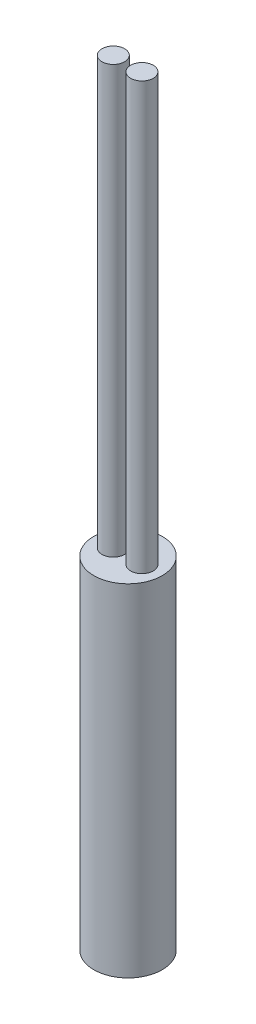
SolidWorks part; units mm, degrees
ref_plane "前视基准面" through (0, 0, 0) normal (0, 0, 1) x (1, 0, 0)
ref_plane "上视基准面" through (0, 0, 0) normal (0, 1, 0) x (1, 0, 0)
ref_plane "右视基准面" through (0, 0, 0) normal (1, 0, 0) x (0, 0, -1)
other "Configuration Table"
sketch "草图1" plane through (0, 0, 0) normal (0, 1, 0) x (1, 0, 0)
  circle A0 centre (0, 0) radius 10.5
  dimension "D1" = 21
extrude "凸台-拉伸1" add sketch "草图1" along normal blind 80
sketch "草图2" plane through (0, 80, 0) normal (0, 1, 0) x (1, 0, 0)
  line L0 (0, 0) -> (0, 10.5)
  circle A0 centre (3.3549, -0.0901) radius 2.6498
  circle A1 centre (0, 0) radius 10.5 construction
  circle A2 centre (-3.3549, -0.0901) radius 2.6498
extrude "凸台-拉伸2" add sketch "草图2" along normal blind 100 contours A2 | A0
sketch "草图3" plane through (0, 0, 0) normal (0, -1, 0) x (1, 0, 0)
  circle A0 centre (0, 0) radius 8
  circle A1 centre (0, 0) radius 10.5
  dimension "D1" = 16
extrude "切除-拉伸1" cut sketch "草图3" against normal through all
